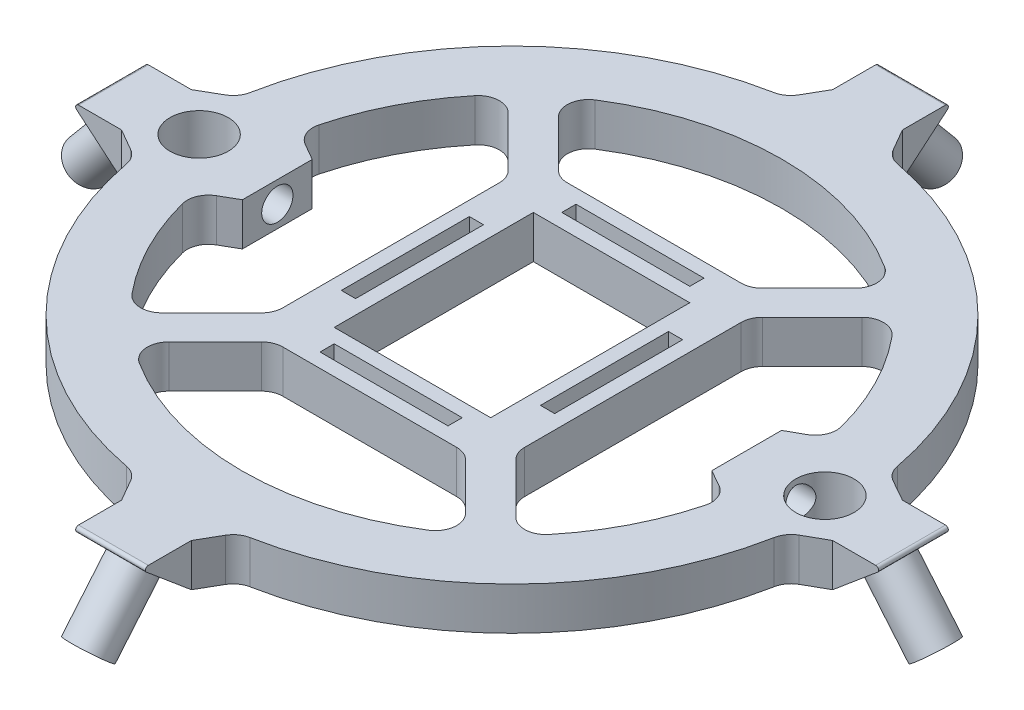
SolidWorks part; units mm, degrees
ref_plane "Front Plane" through (0, 0, 0) normal (0, 0, 1) x (1, 0, 0)
ref_plane "Top Plane" through (0, 0, 0) normal (0, 1, 0) x (1, 0, 0)
ref_plane "Right Plane" through (0, 0, 0) normal (1, 0, 0) x (0, 0, -1)
sketch "Sketch1" plane through (0, 0, 0) normal (0, 1, 0) x (1, 0, 0)
  line L2 (-13.97, 17.78) -> (13.97, 17.78)
  line L3 (-13.97, 17.78) -> (-13.97, -17.78)
  line L4 (-13.97, -17.78) -> (13.97, -17.78)
  line L5 (13.97, 17.78) -> (13.97, -17.78)
  line L6 (-13.97, 17.78) -> (13.97, -17.78) construction
  line L7 (-13.97, -17.78) -> (13.97, 17.78) construction
  point P3 (0, 0)
  dimension "D1" = 35.56
  dimension "D2" = 27.94
extrude "Extrude-Thin1" add sketch "Sketch1" along normal mid plane 7.62 thin thin type one direction wall 7.62
sketch "Sketch2" plane through (0, 0, 0) normal (0, 1, 0) x (1, 0, 0)
  line L4 (0, -4.191) -> (0, 4.191) construction
  line L5 (47.326, -9.2548) -> (41.91, -6.2325)
  line L6 (-47.3075, -9.3487) -> (-41.91, -6.2325)
  line L9 (-41.91, -6.2325) -> (-41.91, 6.2325)
  line L10 (-41.91, 6.2325) -> (-47.3075, 9.3487)
  line L11 (-21.59, -20.9099) -> (-34.4367, -33.7566)
  line L12 (-21.59, 25.4) -> (-21.59, -25.4) construction
  line L13 (-17.0999, -25.4) -> (-29.6948, -37.9949)
  line L14 (-21.59, -25.4) -> (21.59, -25.4) construction
  line L15 (0, 0) -> (50000, 0) construction
  line L16 (0, 0) -> (0, -50000) construction
  line L17 (-58.1025, 9.3487) -> (-63.5, 6.2325)
  line L18 (-63.5, 6.2325) -> (-63.5, -6.2325)
  line L19 (-21.59, -20.9099) -> (-17.0999, -25.4)
  line L20 (-19.3449, -23.1549) -> (-27.6686, -31.4786) construction
  line L21 (-17.0999, 25.4) -> (-29.6948, 37.9949)
  line L22 (-21.59, 20.9099) -> (-34.4367, 33.7566)
  line L23 (17.0999, -25.4) -> (29.6948, -37.9949)
  line L24 (21.59, -20.9099) -> (34.4367, -33.7566)
  line L25 (21.59, 20.9099) -> (34.4367, 33.7566)
  line L26 (17.0999, 25.4) -> (29.6948, 37.9949)
  line L27 (-21.59, 20.9099) -> (-17.0999, 25.4)
  line L28 (17.0999, 25.4) -> (21.59, 20.9099)
  line L29 (21.59, -20.9099) -> (17.0999, -25.4)
  line L30 (-63.5, -6.2325) -> (-58.1025, -9.3487)
  line L31 (41.91, -6.2325) -> (41.91, 6.2325)
  line L32 (41.91, 6.2325) -> (47.326, 9.2548)
  line L33 (58.1149, 9.2711) -> (63.5, 6.2325)
  line L34 (63.5, 6.2325) -> (63.5, -6.2325)
  line L35 (63.5, -6.2325) -> (58.1149, -9.2711)
  line L36 (-6.2325, 63.5) -> (-9.3487, 58.1025)
  line L37 (6.2325, 63.5) -> (-6.2325, 63.5)
  line L38 (9.3487, 58.1025) -> (6.2325, 63.5)
  line L39 (9.3487, -58.1025) -> (6.2325, -63.5)
  line L40 (6.2325, -63.5) -> (-6.2325, -63.5)
  line L41 (-6.2325, -63.5) -> (-9.3487, -58.1025)
  circle A1 centre (55.88, 0) radius 5.207
  circle A4 centre (-55.88, 0) radius 5.207
  circle A9 centre (-52.705, 0) radius 10.795 construction
  arc A10 (-58.1025, 9.3487) -> (-9.3487, 58.1025) centre (0, 0) cw
  arc A11 (47.326, 9.2548) -> (34.4367, 33.7566) centre (0, 0) ccw
  arc A12 (47.326, -9.2548) -> (34.4367, -33.7566) centre (0, 0) cw
  arc A13 (-58.1025, -9.3487) -> (-9.3487, -58.1025) centre (0, 0) ccw
  arc A14 (-34.4367, 33.7566) -> (-47.3075, 9.3487) centre (0, 0) ccw
  arc A15 (29.6948, -37.9949) -> (-29.6948, -37.9949) centre (0, 0) cw
  arc A16 (-34.4367, -33.7566) -> (-47.3075, -9.3487) centre (0, 0) cw
  arc A17 (29.6948, 37.9949) -> (-29.6948, 37.9949) centre (0, 0) ccw
  arc A18 (9.3487, -58.1025) -> (58.1149, -9.2711) centre (0, 0) ccw
  arc A19 (9.3487, 58.1025) -> (58.1149, 9.2711) centre (0, 0) cw
  point P59 (0, 0)
  dimension "D1" = 55.88
  dimension "D3" = 10.414
  dimension "D2" = 6.35
  dimension "D4" = 2
  dimension "D6" = 45
  dimension "D7" = 13.97
  dimension "D8" = 10.795
extrude "Boss-Extrude1" add sketch "Sketch2" along normal mid plane 7.62
fillet "Fillet3" radius 3.81 28 edges at (-58.1025, 0, -9.3487) (-58.1025, 0, 9.3487) (-47.3075, 0, -9.3487) (-47.3075, 0, 9.3487) (-21.59, 0, 20.9099) (-34.4367, 0, 33.7566) (-29.6948, 0, 37.9949) (29.6948, 0, 37.9949) (17.0999, 0, 25.4) (-17.0999, 0, 25.4) (34.4367, 0, 33.7566) (21.59, 0, 20.9099) (47.326, 0, 9.2548) (47.326, 0, -9.2548) (34.4367, 0, -33.7566) (21.59, 0, -20.9099) (17.0999, 0, -25.4) (-21.59, 0, -20.9099) (-17.0999, 0, -25.4) (29.6948, 0, -37.9949) (-29.6948, 0, -37.9949) (-34.4367, 0, -33.7566) (9.3487, 0, -58.1025) (-9.3487, 0, -58.1025) (-9.3487, 0, 58.1025) (9.3487, 0, 58.1025) (58.1149, 0, -9.2711) (58.1149, 0, 9.2711)
sketch "Sketch6" plane through (0, 3.81, 0) normal (0, 1, 0) x (1, 0, 0)
  line L0 (0, -17.78) -> (0, -25.4) construction
  line L1 (-13.97, -17.78) -> (13.97, -17.78) construction
  line L2 (-15.5217, -25.4) -> (15.5217, -25.4) construction
  line L3 (0, 0) -> (50000, 0) construction
  line L4 (-11.43, -20.32) -> (11.43, -20.32)
  line L5 (-11.43, -20.32) -> (-11.43, -22.86)
  line L6 (-11.43, -22.86) -> (11.43, -22.86)
  line L7 (11.43, -20.32) -> (11.43, -22.86)
  line L8 (-11.43, -20.32) -> (11.43, -22.86) construction
  line L9 (-11.43, -22.86) -> (11.43, -20.32) construction
  line L10 (-11.43, 22.86) -> (11.43, 22.86)
  line L11 (11.43, 20.32) -> (11.43, 22.86)
  line L12 (-11.43, 20.32) -> (11.43, 20.32)
  line L13 (-11.43, 20.32) -> (-11.43, 22.86)
  line L14 (-21.59, 4.9442) -> (-13.97, 4.9442) construction
  line L15 (-21.59, 19.3317) -> (-21.59, -19.3317) construction
  line L16 (-13.97, 17.78) -> (-13.97, -17.78) construction
  line L17 (0, 0) -> (0, 50000) construction
  line L18 (-19.05, 11.43) -> (-16.51, 11.43)
  line L19 (-19.05, 11.43) -> (-19.05, -11.43)
  line L20 (-19.05, -11.43) -> (-16.51, -11.43)
  line L21 (-16.51, 11.43) -> (-16.51, -11.43)
  line L22 (-19.05, 11.43) -> (-16.51, -11.43) construction
  line L23 (-19.05, -11.43) -> (-16.51, 11.43) construction
  line L24 (19.05, -11.43) -> (16.51, -11.43)
  line L25 (16.51, 11.43) -> (16.51, -11.43)
  line L26 (19.05, 11.43) -> (19.05, -11.43)
  line L27 (19.05, 11.43) -> (16.51, 11.43)
  point P6 (0, -21.59)
  point P11 (0, -21.59)
  point P25 (-17.78, 0)
  point P30 (-17.78, 4.9442)
  dimension "D1" = 2.54
  dimension "D2" = 22.86
extrude "Cut-Extrude2" cut sketch "Sketch6" against normal up to next
sketch "Sketch7" plane through (21.59, 0, 0) normal (1, 0, 0) x (0, 0, -1)
  circle A0 centre (0, 0) radius 2.794
  dimension "D1" = 5.588
extrude "Cut-Extrude5" cut sketch "Sketch7" along normal up to surface (29.8961 mm away) contours A0
sketch "Sketch8" plane through (-21.59, 0, 0) normal (-1, 0, 0) x (0, 0, 1)
  circle A0 centre (0, 0) radius 2.794
  dimension "D1" = 5.588
extrude "Cut-Extrude6" cut sketch "Sketch8" along normal up to surface (29.8961 mm away)
sketch "Sketch9" plane through (0, 0, 0) normal (0, 0, 1) x (1, 0, 0)
  line L6 (-63.5, 3.81) -> (-72.5812, 3.81)
  line L12 (-72.5812, 3.81) -> (-63.5, -3.81)
  line L13 (-63.5, -3.81) -> (-63.5, 3.81)
  dimension "D1" = 50
extrude "Boss-Extrude3" add sketch "Sketch9" along normal up to vertex (6.2325 mm away) and the other way up to vertex (6.2325 mm away) contours L6 L12 L13
sketch "Sketch12" plane through (0, 0, 0) normal (1, 0, 0) x (0, 0, -1)
  line L0 (-63.5, 3.81) -> (-72.5812, 3.81)
  line L1 (-72.5812, 3.81) -> (-63.5, -3.81)
  line L2 (-63.5, -3.81) -> (-63.5, 3.81)
  line L3 (0, 4.191) -> (0, -4.191) construction
  line L4 (63.5, -3.81) -> (63.5, 3.81)
  line L5 (63.5, 3.81) -> (72.5812, 3.81)
  line L6 (72.5812, 3.81) -> (63.5, -3.81)
  dimension "D1" = 50
extrude "Boss-Extrude5" add sketch "Sketch12" along normal up to vertex (6.2325 mm away) and the other way up to vertex (6.2325 mm away)
sketch "Sketch13" plane through (0, 0, 0) normal (0, 0, 1) x (1, 0, 0)
  line L0 (63.5, -3.81) -> (63.5, 3.81)
  line L1 (63.5, 3.81) -> (72.5812, 3.81)
  line L2 (72.5812, 3.81) -> (63.5, -3.81)
  dimension "D1" = 50
extrude "Boss-Extrude6" add sketch "Sketch13" along normal up to vertex (6.2325 mm away) and the other way up to vertex (6.2325 mm away)
fillet "Fillet2" radius 0.508 4 edges at (-72.5812, 3.81, 0) (0, 3.81, 72.5812) (0, 3.81, -72.5812) (72.5812, 3.81, 0)
sketch "Sketch10" plane through (-28.1127, -33.5034, 0) normal (-0.6428, -0.766, 0) x (0.766, -0.6428, 0)
  line L0 (-56.6537, 6.2325) -> (-46.1948, 6.2325) construction
  line L1 (-58.0494, 6.2325) -> (-58.0494, -6.2325) construction
  circle A0 centre (-51.4242, 0) radius 3.81
  circle A1 centre (-51.4242, 0) radius 2.7305
  point P5 (-51.4242, 6.2325)
  point P8 (-58.0494, 0)
  dimension "D1" = 7.62
  dimension "D2" = 5.461
extrude "Boss-Extrude4" add sketch "Sketch10" along normal blind 12.7
pattern_circular "CirPattern2" count 4 over 360 about axis through (0, 0, 0) along (0, 1, 0) of "Boss-Extrude4"
